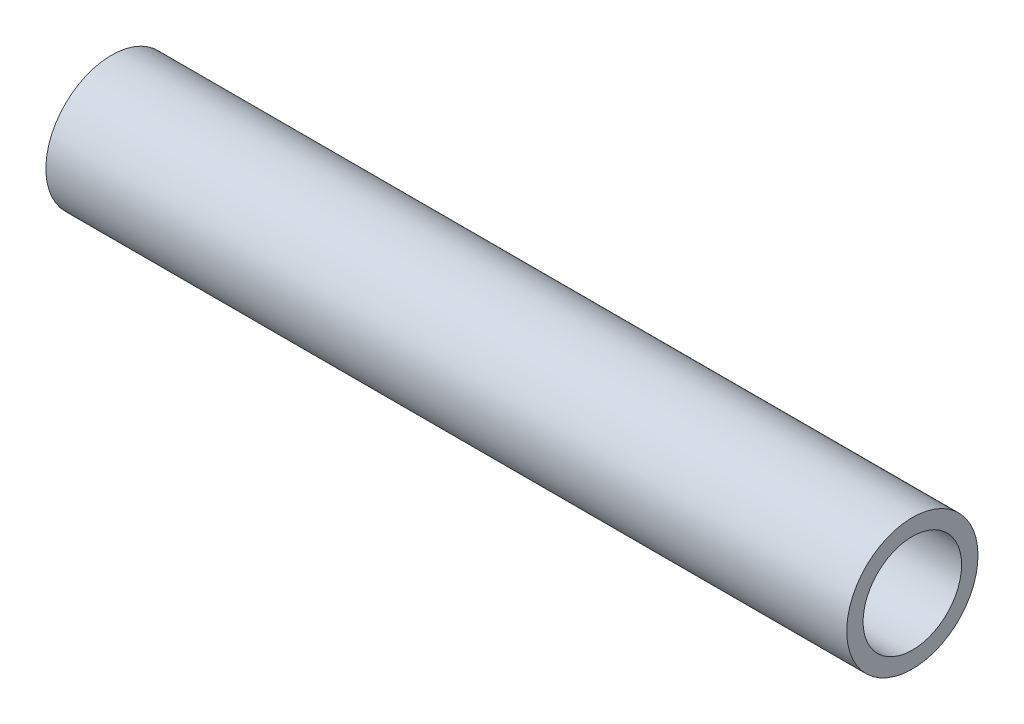
SolidWorks part; units mm, degrees
ref_plane "Front Plane" through (0, 0, 0) normal (0, 0, 1) x (1, 0, 0)
ref_plane "Top Plane" through (0, 0, 0) normal (0, 1, 0) x (1, 0, 0)
ref_plane "Right Plane" through (0, 0, 0) normal (1, 0, 0) x (0, 0, -1)
sketch "Sketch1" plane through (0, 0, 0) normal (1, 0, 0) x (0, -1, 0)
  circle A0 centre (0, 0) radius 4.7625
  circle A1 centre (0, 0) radius 6.35
  dimension "D1" = 12.7
  dimension "D2" = 9.525
extrude "Boss-Extrude1" add sketch "Sketch1" along normal blind 77.47
